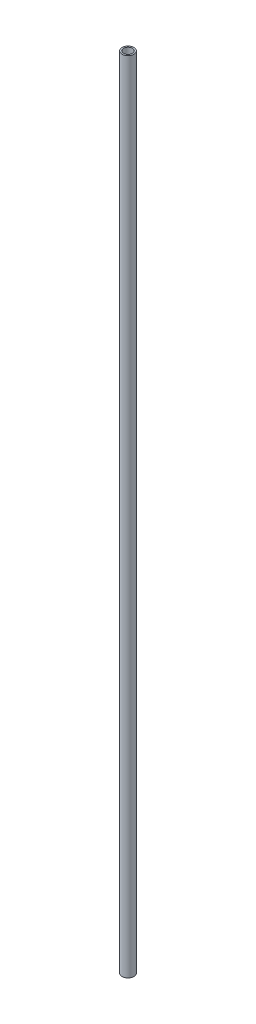
SolidWorks part; units mm, degrees
ref_plane "Front Plane" through (0, 0, 0) normal (0, 0, 1) x (1, 0, 0)
ref_plane "Top Plane" through (0, 0, 0) normal (0, 1, 0) x (1, 0, 0)
ref_plane "Right Plane" through (0, 0, 0) normal (1, 0, 0) x (0, 0, -1)
sketch "Sketch1" plane through (0, 0, 0) normal (0, 0, 1) x (1, 0, 0)
  line L0 (0, 0) -> (0, 540)
  point P6 (0, 540)
  dimension "D1" = 540
sketch "Sketch2" plane through (0, 0, 0) normal (0, 1, 0) x (1, 0, 0)
  circle A0 centre (0, 0) radius 4
  circle A1 centre (0, 0) radius 3
  dimension "D1" = 6
  dimension "D2" = 8
sweep "Sweep1" add profiles "Sketch2" path "Sketch1"
